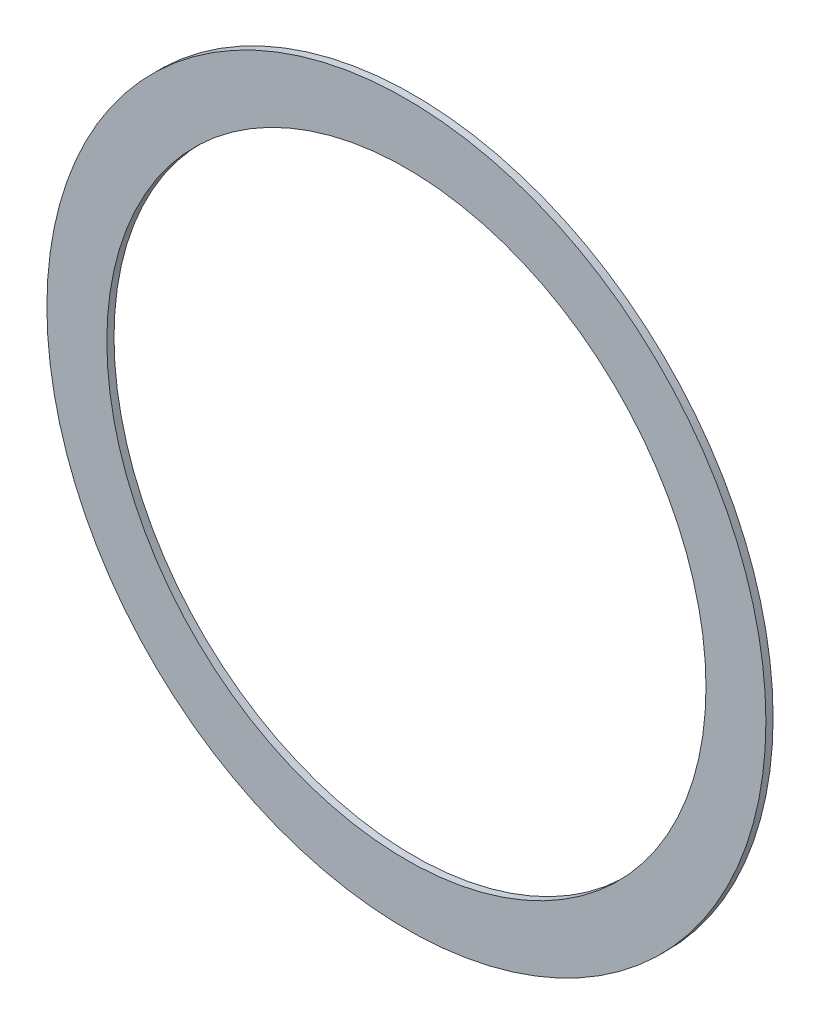
SolidWorks part; units mm, degrees
material "VITON"
ref_plane "Front Plane" through (0, 0, 0) normal (0, 0, 1) x (1, 0, 0)
ref_plane "Top Plane" through (0, 0, 0) normal (0, 1, 0) x (1, 0, 0)
ref_plane "Right Plane" through (0, 0, 0) normal (1, 0, 0) x (0, 0, -1)
sketch "Base Sketch" plane through (0, 0, 0) normal (0, 0, 1) x (1, 0, 0)
  circle A0 centre (0, 0) radius 19.05
  circle A1 centre (0, 0) radius 15.875
  dimension "D1" = 38.1
  dimension "D2" = 31.75
extrude "Base Extrude" add sketch "Base Sketch" against normal blind 0.381
